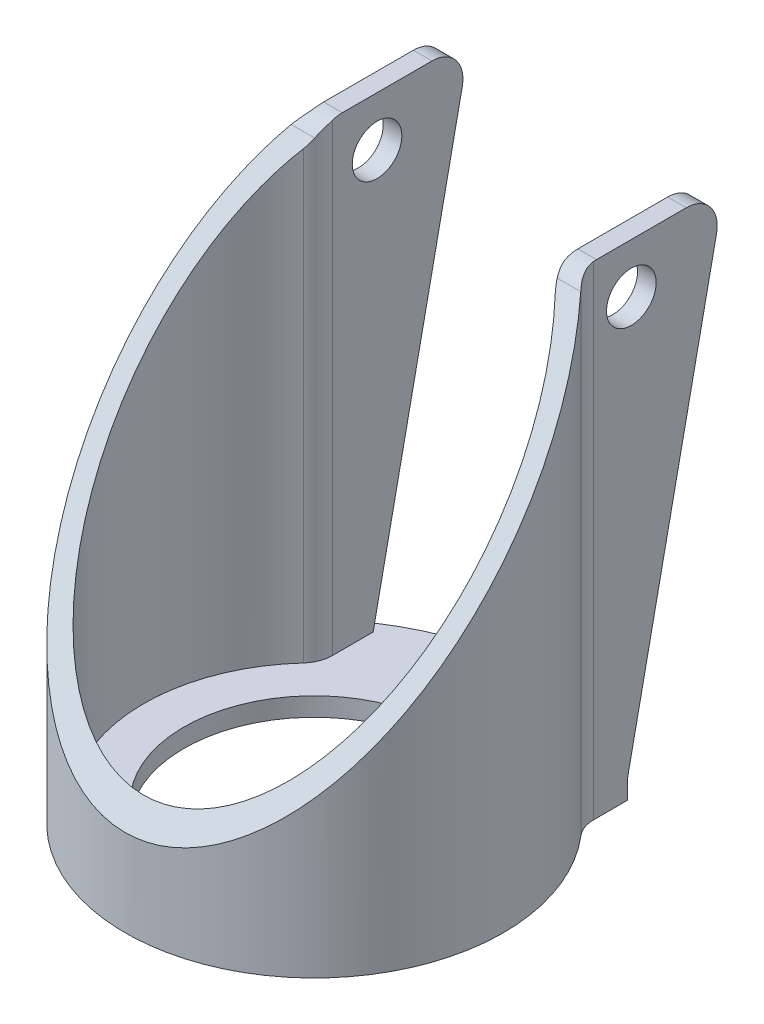
SolidWorks part; units mm, degrees
ref_plane "Front Plane" through (0, 0, 0) normal (0, 0, 1) x (1, 0, 0)
ref_plane "Top Plane" through (0, 0, 0) normal (0, 1, 0) x (1, 0, 0)
ref_plane "Right Plane" through (0, 0, 0) normal (1, 0, 0) x (0, 0, -1)
sketch "Sketch1" plane through (0, 0, 0) normal (0, 1, 0) x (1, 0, 0)
  line L2 (22, 28.4956) -> (22, 21.1246)
  line L4 (-22, 28.4956) -> (-22, 21.1246)
  circle A1 centre (0, 0) radius 30.5
  arc A2 (22, 28.4956) -> (-22, 28.4956) centre (0, 0) ccw
  point P9 (-22, 28.4956)
extrude "Boss-Extrude1" add sketch "Sketch1" along normal blind 3 contours A1 | L2 A2 L4 A1
sketch "Sketch2" plane through (0, 3, 0) normal (0, 1, 0) x (1, 0, 0)
  line L0 (-22, 21.1246) -> (-22, 28.4956)
  line L1 (22, 21.1246) -> (22, 28.4956)
  line L2 (-22, 28.4956) -> (-19, 28.4956)
  line L3 (22, 28.4956) -> (19, 28.4956)
  line L4 (-19, 19.8809) -> (-19, 28.4956)
  line L5 (19, 19.8809) -> (19, 28.4956)
  arc A0 (22, 21.1246) -> (-22, 21.1246) centre (0, 0) cw
  arc A1 (19, 19.8809) -> (-19, 19.8809) centre (0, 0) cw
  arc A2 (-22, 21.1246) -> (22, 21.1246) centre (0, 0) ccw construction
ref_plane "Plane1" through (0, 78, 0) normal (0, 1, 0) x (1, 0, 0)
sketch "Sketch3" plane through (0, 78, 0) normal (0, 1, 0) x (1, 0, 0)
  line L1 (-22, 21.1246) -> (-22, 44.1246)
  line L2 (22, 21.1246) -> (22, 44.1246)
  line L3 (22, 44.1246) -> (19, 44.1246)
  line L4 (19, 44.1246) -> (19, 19.8809)
  line L5 (-22, 44.1246) -> (-19, 44.1246)
  line L6 (-19, 44.1246) -> (-19, 19.8809)
  arc A0 (19, 19.8809) -> (-19, 19.8809) centre (0, 0) cw
  arc A2 (22, 21.1246) -> (-22, 21.1246) centre (0, 0) cw
loft "Loft1" add profiles "Sketch2", "Sketch3"
sketch "Sketch9" plane through (0, 0, 0) normal (1, 0, 0) x (0, 0, -1)
  line L0 (-30.5, 14) -> (21.1246, 78)
  line L1 (-30.5, 78) -> (-30.5, 0) construction
  line L2 (33.7011, 78) -> (-33.7011, 78) construction
  line L3 (21.1246, 78) -> (21.1246, 0) construction
  line L4 (-30.5, 0) -> (21.1246, 0) construction
  line L5 (-30.5, 14) -> (-30.5, 78)
  line L6 (-30.5, 78) -> (21.1246, 78)
  dimension "D1" = 14
extrude "Cut-Extrude1" cut sketch "Sketch9" against normal through all and the other way through all
sketch "Sketch10" plane through (-22, 0, 0) normal (-1, 0, 0) x (0, 0, 1)
  line L0 (-44.1246, 78) -> (-21.1246, 78) construction
  line L1 (-21.1246, 78) -> (-21.1246, 0) construction
  circle A0 centre (-29.1246, 70) radius 4
  dimension "D1" = 8
  dimension "D2" = 8
extrude "Cut-Extrude2" cut sketch "Sketch10" against normal through all
sketch "Sketch11" plane through (0, 3, 0) normal (0, 1, 0) x (1, 0, 0)
  circle A0 centre (0, 0) radius 21
extrude "Cut-Extrude3" cut sketch "Sketch11" against normal through all
fillet "Fillet1" radius 5 2 edges
fillet "Fillet2" radius 5 2 edges
fillet "Fillet3" radius 5 4 edges
